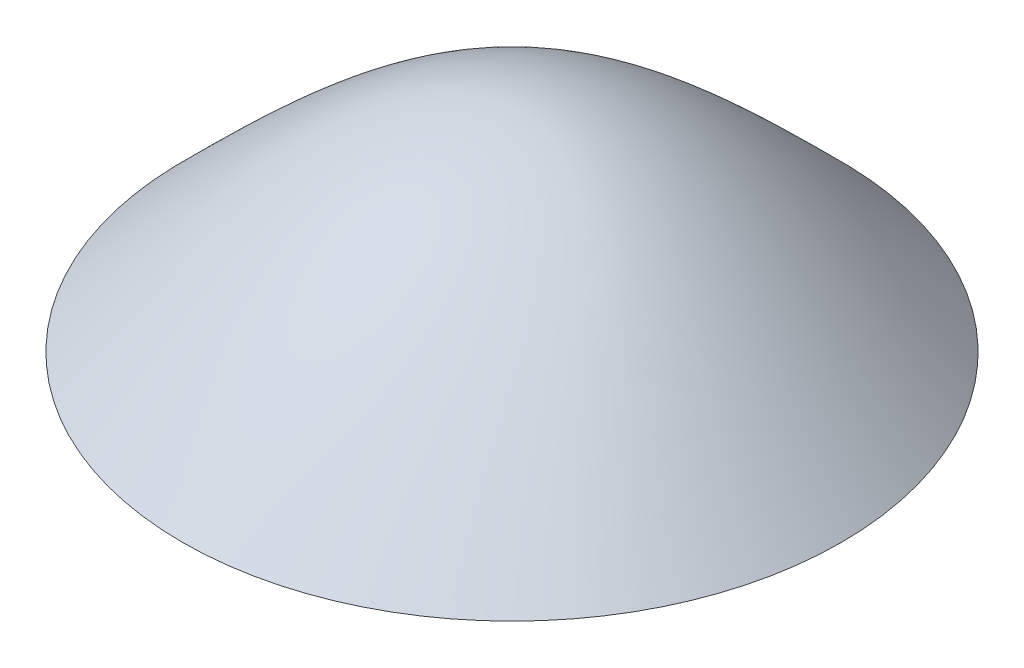
SolidWorks part; units mm, degrees
ref_plane "前视基准面" through (0, 0, 0) normal (0, 0, 1) x (1, 0, 0)
ref_plane "上视基准面" through (0, 0, 0) normal (0, 1, 0) x (1, 0, 0)
ref_plane "右视基准面" through (0, 0, 0) normal (1, 0, 0) x (0, 0, -1)
curve "曲线1"
  spline degree 3 poles (0, 1, 0) (0.0067, 1, 0) (0.02, 0.9999, 0) (0.04, 0.9993, 0) (0.06, 0.9983, 0) (0.08, 0.9969, 0) (0.1, 0.9951, 0) (0.12, 0.9929, 0) (0.14, 0.9903, 0) (0.16, 0.9873, 0) (0.18, 0.9839, 0) (0.2, 0.9801, 0) (0.22, 0.976, 0) (0.24, 0.9714, 0) (0.26, 0.9664, 0) (0.28, 0.9611, 0) (0.3001, 0.9554, 0) (0.3201, 0.9493, 0) (0.3401, 0.9428, 0) (0.3601, 0.9359, 0) (0.3801, 0.9287, 0) (0.4001, 0.9211, 0) (0.4201, 0.9131, 0) (0.4401, 0.9048, 0) (0.4601, 0.8961, 0) (0.4801, 0.887, 0) (0.5001, 0.8776, 0) (0.5201, 0.8678, 0) (0.5401, 0.8577, 0) (0.5601, 0.8473, 0) (0.5801, 0.8365, 0) (0.6001, 0.8254, 0) (0.6201, 0.8139, 0) (0.6401, 0.8021, 0) (0.6601, 0.79, 0) (0.6801, 0.7776, 0) (0.7001, 0.7648, 0) (0.7201, 0.7518, 0) (0.7401, 0.7385, 0) (0.7601, 0.7248, 0) (0.7801, 0.7109, 0) (0.8001, 0.6967, 0) (0.8201, 0.6822, 0) (0.8401, 0.6675, 0) (0.8601, 0.6524, 0) (0.8801, 0.6371, 0) (0.9001, 0.6216, 0) (0.9201, 0.6058, 0) (0.9401, 0.5898, 0) (0.9601, 0.5735, 0) (0.9801, 0.557, 0) (1.0001, 0.5403, 0) (1.0201, 0.5234, 0) (1.0401, 0.5062, 0) (1.06, 0.4889, 0) (1.08, 0.4713, 0) (1.1, 0.4536, 0) (1.12, 0.4357, 0) (1.14, 0.4176, 0) (1.16, 0.3993, 0) (1.18, 0.3809, 0) (1.2, 0.3623, 0) (1.22, 0.3436, 0) (1.24, 0.3248, 0) (1.26, 0.3058, 0) (1.28, 0.2867, 0) (1.3, 0.2675, 0) (1.32, 0.2482, 0) (1.34, 0.2287, 0) (1.36, 0.2092, 0) (1.38, 0.1896, 0) (1.4, 0.17, 0) (1.42, 0.1502, 0) (1.44, 0.1304, 0) (1.46, 0.1106, 0) (1.48, 0.0907, 0) (1.5, 0.0707, 0) (1.52, 0.0508, 0) (1.54, 0.0308, 0) (1.5533, 0.0175, 0) (1.56, 0.0108, 0) knots 0 0 0 0 0.010556 0.021115 0.031684 0.042265 0.052862 0.063481 0.074124 0.084796 0.095501 0.106243 0.117025 0.127851 0.138724 0.149648 0.160627 0.171662 0.182757 0.193916 0.20514 0.216432 0.227794 0.23923 0.25074 0.262327 0.273993 0.285739 0.297566 0.309476 0.321469 0.333548 0.345712 0.357963 0.3703 0.382725 0.395237 0.407836 0.420523 0.433297 0.446158 0.459105 0.472138 0.485255 0.498457 0.511742 0.52511 0.538558 0.552085 0.565691 0.579374 0.593132 0.606963 0.620866 0.634838 0.648879 0.662985 0.677155 0.691387 0.705677 0.720025 0.734427 0.748882 0.763386 0.777937 0.792533 0.807171 0.821848 0.836561 0.851308 0.866086 0.880891 0.895723 0.910576 0.925449 0.940338 0.955241 0.970154 0.985075 1 1 1 1
sketch "草图1" plane through (0, 0, 0) normal (0, 0, 1) x (1, 0, 0)
  line L0 (0, 1) -> (0, 0)
  line L1 (0, 0) -> (1.56, 0.0108)
  spline S0 degree 3 poles (25.8069, 2000.6674) (-3.9317, -5.9425) (-1.8935, 1.0595) (0.04, 0.9993) (0.06, 0.9983) (0.08, 0.9969) (0.1, 0.9951) (0.12, 0.9929) (0.14, 0.9903) (0.16, 0.9873) (0.18, 0.9839) (0.2, 0.9801) (0.22, 0.976) (0.24, 0.9714) (0.26, 0.9664) (0.28, 0.9611) (0.3001, 0.9554) (0.3201, 0.9493) (0.3401, 0.9428) (0.3601, 0.9359) (0.3801, 0.9287) (0.4001, 0.9211) (0.4201, 0.9131) (0.4401, 0.9048) (0.4601, 0.8961) (0.4801, 0.887) (0.5001, 0.8776) (0.5201, 0.8678) (0.5401, 0.8577) (0.5601, 0.8473) (0.5801, 0.8365) (0.6001, 0.8254) (0.6201, 0.8139) (0.6401, 0.8021) (0.6601, 0.79) (0.6801, 0.7776) (0.7001, 0.7648) (0.7201, 0.7518) (0.7401, 0.7385) (0.7601, 0.7248) (0.7801, 0.7109) (0.8001, 0.6967) (0.8201, 0.6822) (0.8401, 0.6675) (0.8601, 0.6524) (0.8801, 0.6371) (0.9001, 0.6216) (0.9201, 0.6058) (0.9401, 0.5898) (0.9601, 0.5735) (0.9801, 0.557) (1.0001, 0.5403) (1.0201, 0.5234) (1.0401, 0.5062) (1.06, 0.4889) (1.08, 0.4713) (1.1, 0.4536) (1.12, 0.4357) (1.14, 0.4176) (1.16, 0.3993) (1.18, 0.3809) (1.2, 0.3623) (1.22, 0.3436) (1.24, 0.3248) (1.26, 0.3058) (1.28, 0.2867) (1.3, 0.2675) (1.32, 0.2482) (1.34, 0.2287) (1.36, 0.2092) (1.38, 0.1896) (1.4, 0.17) (1.42, 0.1502) (1.44, 0.1304) (1.46, 0.1106) (1.48, 0.0907) (1.5, 0.0707) (1.52, 0.0508) (8.7406, -7.164) (14.6403, -15.6868) (1436.913, 1392.6091) knots -3.030685 -3.030685 -3.030685 -3.030685 0.010556 0.021115 0.031684 0.042265 0.052862 0.063481 0.074124 0.084796 0.095501 0.106243 0.117025 0.127851 0.138724 0.149648 0.160627 0.171662 0.182757 0.193916 0.20514 0.216432 0.227794 0.23923 0.25074 0.262327 0.273993 0.285739 0.297566 0.309476 0.321469 0.333548 0.345712 0.357963 0.3703 0.382725 0.395237 0.407836 0.420523 0.433297 0.446158 0.459105 0.472138 0.485255 0.498457 0.511742 0.52511 0.538558 0.552085 0.565691 0.579374 0.593132 0.606963 0.620866 0.634838 0.648879 0.662985 0.677155 0.691387 0.705677 0.720025 0.734427 0.748882 0.763386 0.777937 0.792533 0.807171 0.821848 0.836561 0.851308 0.866086 0.880891 0.895723 0.910576 0.925449 0.940338 0.955241 0.970154 0.985075 17.116148 17.116148 17.116148 17.116148 only from (0, 1) to (1.56, 0.0108) construction
  spline S1 degree 3 poles (0, 1) (0.0067, 1) (0.02, 0.9999) (0.04, 0.9993) (0.06, 0.9983) (0.08, 0.9969) (0.1, 0.9951) (0.12, 0.9929) (0.14, 0.9903) (0.16, 0.9873) (0.18, 0.9839) (0.2, 0.9801) (0.22, 0.976) (0.24, 0.9714) (0.26, 0.9664) (0.28, 0.9611) (0.3001, 0.9554) (0.3201, 0.9493) (0.3401, 0.9428) (0.3601, 0.9359) (0.3801, 0.9287) (0.4001, 0.9211) (0.4201, 0.9131) (0.4401, 0.9048) (0.4601, 0.8961) (0.4801, 0.887) (0.5001, 0.8776) (0.5201, 0.8678) (0.5401, 0.8577) (0.5601, 0.8473) (0.5801, 0.8365) (0.6001, 0.8254) (0.6201, 0.8139) (0.6401, 0.8021) (0.6601, 0.79) (0.6801, 0.7776) (0.7001, 0.7648) (0.7201, 0.7518) (0.7401, 0.7385) (0.7601, 0.7248) (0.7801, 0.7109) (0.8001, 0.6967) (0.8201, 0.6822) (0.8401, 0.6675) (0.8601, 0.6524) (0.8801, 0.6371) (0.9001, 0.6216) (0.9201, 0.6058) (0.9401, 0.5898) (0.9601, 0.5735) (0.9801, 0.557) (1.0001, 0.5403) (1.0201, 0.5234) (1.0401, 0.5062) (1.06, 0.4889) (1.08, 0.4713) (1.1, 0.4536) (1.12, 0.4357) (1.14, 0.4176) (1.16, 0.3993) (1.18, 0.3809) (1.2, 0.3623) (1.22, 0.3436) (1.24, 0.3248) (1.26, 0.3058) (1.28, 0.2867) (1.3, 0.2675) (1.32, 0.2482) (1.34, 0.2287) (1.36, 0.2092) (1.38, 0.1896) (1.4, 0.17) (1.42, 0.1502) (1.44, 0.1304) (1.46, 0.1106) (1.48, 0.0907) (1.5, 0.0707) (1.52, 0.0508) (1.54, 0.0308) (1.5533, 0.0175) (1.56, 0.0108) knots 0 0 0 0 0.010556 0.021115 0.031684 0.042265 0.052862 0.063481 0.074124 0.084796 0.095501 0.106243 0.117025 0.127851 0.138724 0.149648 0.160627 0.171662 0.182757 0.193916 0.20514 0.216432 0.227794 0.23923 0.25074 0.262327 0.273993 0.285739 0.297566 0.309476 0.321469 0.333548 0.345712 0.357963 0.3703 0.382725 0.395237 0.407836 0.420523 0.433297 0.446158 0.459105 0.472138 0.485255 0.498457 0.511742 0.52511 0.538558 0.552085 0.565691 0.579374 0.593132 0.606963 0.620866 0.634838 0.648879 0.662985 0.677155 0.691387 0.705677 0.720025 0.734427 0.748882 0.763386 0.777937 0.792533 0.807171 0.821848 0.836561 0.851308 0.866086 0.880891 0.895723 0.910576 0.925449 0.940338 0.955241 0.970154 0.985075 1 1 1 1
revolve "旋转1" add sketch "草图1" angle 360 about L0
sketch "草图2" plane through (0, 0, 0) normal (0, 1, 0) x (1, 0, 0)
  line L0 (0, -0.4097) -> (0, 0.4097)
  arc A0 (0, -0.4097) -> (0, 0.4097) centre (0, 0) ccw
revolve "切除-旋转1" cut sketch "草图2" angle 360 about L0
